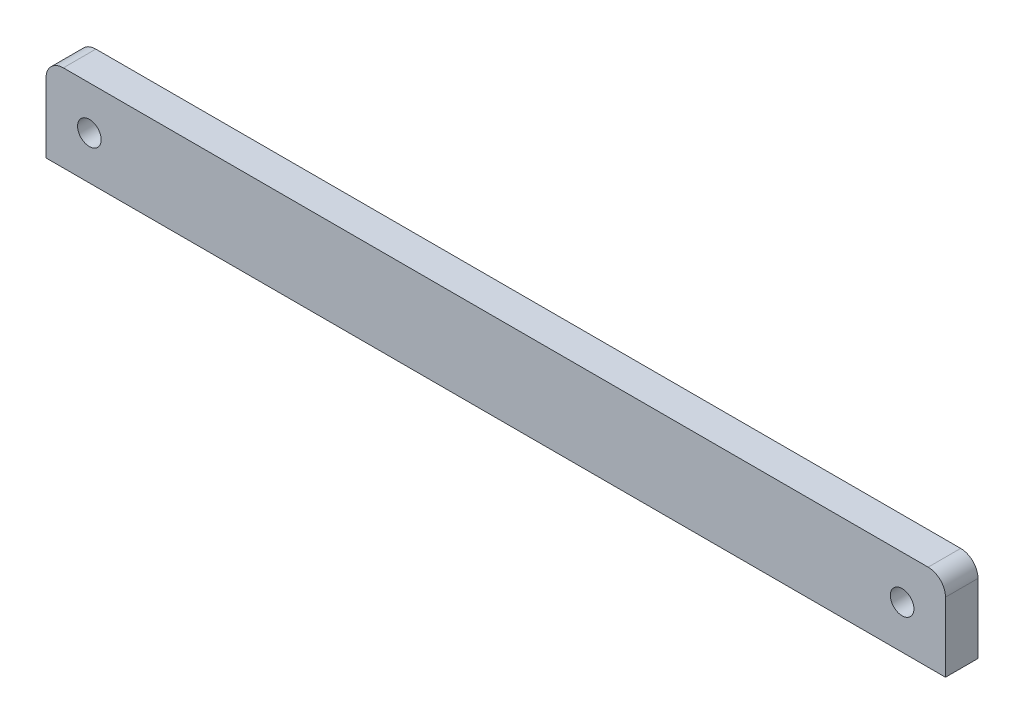
SolidWorks part; units mm, degrees
material "Acrylic (Medium-high impact)"
ref_plane "Front Plane" through (0, 0, 0) normal (0, 0, 1) x (1, 0, 0)
ref_plane "Top Plane" through (0, 0, 0) normal (0, 1, 0) x (1, 0, 0)
ref_plane "Right Plane" through (0, 0, 0) normal (1, 0, 0) x (0, 0, -1)
sketch "Sketch1" plane through (0, 0, 0) normal (0, 0, 1) x (1, 0, 0)
  line L0 (-26.9939, 45.8956) -> (104.7559, 45.8956) construction
  line L1 (-26.9939, 52.2456) -> (104.7559, 52.2456)
  line L2 (-26.9939, 52.2456) -> (-26.9939, 39.5456)
  line L3 (-26.9939, 39.5456) -> (104.7559, 39.5456)
  line L4 (104.7559, 52.2456) -> (104.7559, 39.5456)
  line L5 (-20.6439, 39.5456) -> (-20.6439, 52.2456) construction
  line L6 (98.4059, 39.5456) -> (98.4059, 52.2456) construction
  circle A0 centre (-20.6439, 45.8956) radius 1.7272
  circle A1 centre (98.4059, 45.8956) radius 1.7272
  dimension "D5" = 3.4544
  dimension "D1" = 131.7498
  dimension "D2" = 12.7
  dimension "D3" = 6.35
  dimension "D4" = 6.35
extrude "Boss-Extrude1" add sketch "Sketch1" along normal blind 4.7625
fillet "Fillet1" radius 2.54 2 edges at (104.7559, 52.2456, 2.3813) (-26.9939, 52.2456, 2.3813)
